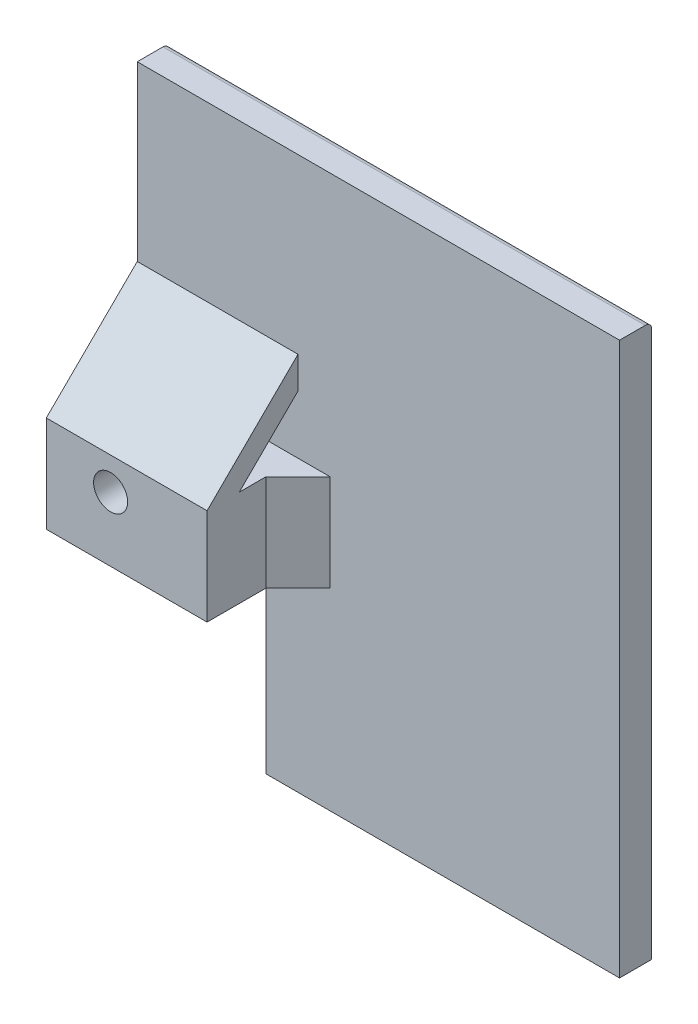
SolidWorks part; units mm, degrees
ref_plane "Front Plane" through (0, 0, 0) normal (0, 0, 1) x (1, 0, 0)
ref_plane "Top Plane" through (0, 0, 0) normal (0, 1, 0) x (1, 0, 0)
ref_plane "Right Plane" through (0, 0, 0) normal (1, 0, 0) x (0, 0, -1)
sketch "Sketch1" plane through (0, 0, 0) normal (0, 0, 1) x (1, 0, 0)
  line L7 (0, 0) -> (20, 0)
  line L8 (0, 0) -> (0, 15)
  line L9 (0, 15) -> (20, 15)
  line L10 (20, 0) -> (20, 15)
  line L11 (20, 15) -> (25, 15)
  line L12 (20, 15) -> (20, 0)
  line L13 (20, 0) -> (25, 0)
  line L14 (25, 15) -> (25, 0)
  circle A0 centre (10, 10) radius 2.65
  dimension "D4" = 5.3
  dimension "D1" = 20
  dimension "D2" = 15
  dimension "D3" = 5
  dimension "D5" = 5
  dimension "D6" = 10
extrude "Boss-Extrude1" add sketch "Sketch1" along normal blind 5 contours L7 L10 L9 L8 A0 | L14 L11 L10 L13
sketch "Sketch2" plane through (0, 0, 0) normal (0, 0, -1) x (-1, 0, 0)
  line L0 (0, 0) -> (-25, 0) construction
  line L1 (-25, 15) -> (-20, 15)
  line L2 (-25, 15) -> (-25, 0)
  line L3 (-25, 0) -> (-20, 0)
  line L4 (-20, 15) -> (-20, 0)
  dimension "D1" = 5
extrude "Boss-Extrude2" add sketch "Sketch2" along normal blind 14.1421
sketch "Sketch3" plane through (25, 0, 0) normal (1, 0, 0) x (0, 0, -1)
  line L0 (-5, 0) -> (14.1421, 0) construction
  line L1 (14.1421, 15) -> (9.1421, 15)
  line L2 (14.1421, 15) -> (14.1421, 0)
  line L3 (14.1421, 0) -> (9.1421, 0)
  line L4 (9.1421, 15) -> (9.1421, 0)
  dimension "D1" = 5
extrude "Boss-Extrude3" add sketch "Sketch3" along normal blind 50
sketch "Sketch4" plane through (0, 15, 0) normal (0, 1, 0) x (1, 0, 0)
  line L0 (20, 14.1421) -> (20, 0) construction
  line L1 (20, 9.1421) -> (75, 9.1421)
  line L2 (20, 9.1421) -> (20, 14.1421)
  line L3 (20, 14.1421) -> (75, 14.1421)
  line L4 (75, 9.1421) -> (75, 14.1421)
  line L5 (75, 9.1421) -> (25, 9.1421) construction
extrude "Boss-Extrude4" add sketch "Sketch4" along normal blind 40.9
sketch "Sketch5" plane through (0, 0, -14.1421) normal (0, 0, -1) x (-1, 0, 0)
  line L0 (-20, 0) -> (-20, 55.9) construction
  line L1 (-20, 29) -> (0, 29)
  line L2 (-20, 29) -> (-20, 55.9)
  line L3 (-20, 55.9) -> (0, 55.9)
  line L4 (0, 29) -> (0, 55.9)
  line L5 (-75, 0) -> (-20, 0) construction
  line L7 (-75, 55.9) -> (-20, 55.9) construction
  dimension "D1" = 29
  dimension "D2" = 20
  dimension "D3" = 0
extrude "Boss-Extrude5" add sketch "Sketch5" against normal blind 5
sketch "Sketch6" plane through (0, 0, 0) normal (-1, 0, 0) x (0, 0, 1)
  line L0 (0, 15) -> (-14.1421, 29)
  line L3 (5, 15) -> (0, 15)
  line L5 (-14.1421, 29) -> (-9.1421, 29)
  line L6 (-9.1421, 29) -> (5, 15)
extrude "Boss-Extrude6" add sketch "Sketch6" against normal up to surface (25 mm away) up to face at (25, 7.5, -2.0711)
chamfer "Chamfer1" distance 5 angle 45 1 edges at (25, 7.5, -9.1421)
fillet "Fillet5" radius 1 1 edges at (37.5, 55.9, -14.1421)
sketch "Sketch7" plane through (0, 0, 0) normal (0, -1, 0) x (1, 0, 0)
  line L0 (20, -14.1421) -> (20, 0) construction
  line L1 (75, -14.1421) -> (20, -14.1421)
  line L2 (75, -14.1421) -> (75, -9.1421)
  line L3 (75, -9.1421) -> (20, -9.1421)
  line L4 (20, -14.1421) -> (20, -9.1421)
  line L5 (75, -9.1421) -> (30, -9.1421) construction
  dimension "D1" = 0
extrude "Boss-Extrude7" add sketch "Sketch7" along normal blind 30
equation "\"D1@Boss-Extrude2\"=sqr(200 )"
